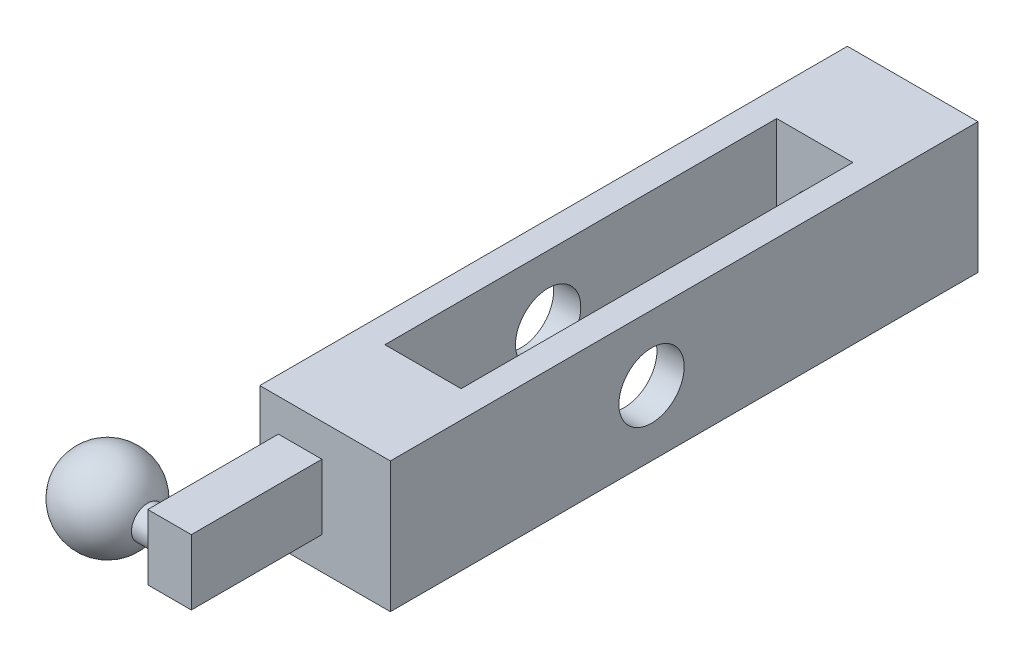
SolidWorks part; units mm, degrees
ref_plane "前视基准面" through (0, 0, 0) normal (0, 0, 1) x (1, 0, 0)
ref_plane "上视基准面" through (0, 0, 0) normal (0, 1, 0) x (1, 0, 0)
ref_plane "右视基准面" through (0, 0, 0) normal (1, 0, 0) x (0, 0, -1)
other "Configuration Table"
sketch "草图1" plane through (0, 0, 0) normal (0, 0, 1) x (1, 0, 0)
  line L1 (3, -3) -> (-3, -3)
  line L2 (3, -3) -> (3, 3)
  line L3 (3, 3) -> (-3, 3)
  line L4 (-3, -3) -> (-3, 3)
  line L5 (3, -3) -> (-3, 3) construction
  line L6 (3, 3) -> (-3, -3) construction
  point P0 (0, 0)
  dimension "D1" = 6
  dimension "D2" = 6
extrude "凸台-拉伸1" add sketch "草图1" along normal blind 27
sketch "草图2" plane through (0, 0, 27) normal (0, 0, 1) x (1, 0, 0)
  line L1 (-2.1448, 1.4955) -> (-0.1448, 1.4955)
  line L2 (-2.1448, 1.4955) -> (-2.1448, -1.5045)
  line L3 (-2.1448, -1.5045) -> (-0.1448, -1.5045)
  line L4 (-0.1448, 1.4955) -> (-0.1448, -1.5045)
  line L5 (-2.1448, 1.4955) -> (-0.1448, -1.5045) construction
  line L6 (-2.1448, -1.5045) -> (-0.1448, 1.4955) construction
  point P0 (-1.1448, -0.0045)
  dimension "D1" = 2
  dimension "D2" = 3
extrude "凸台-拉伸2" add sketch "草图2" along normal blind 6
sketch "草图3" plane through (-2.1448, 0, 0) normal (-1, 0, 0) x (0, 0, 1)
  circle A0 centre (32, 0) radius 0.75
  dimension "D1" = 1.5
  dimension "D2" = 32
extrude "凸台-拉伸3" add sketch "草图3" along normal blind 1
sketch "草图4" plane through (0, 0, 0) normal (0, 1, 0) x (1, 0, 0)
  line L0 (-3.1448, -32) -> (-6.9988, -32)
  line L1 (-3.1448, -31.25) -> (-3.1448, -32.75) construction
  line L2 (-3.1448, -32) -> (-3.1448, -31.25)
  arc A0 (-3.1448, -31.25) -> (-6.9988, -32) centre (-4.9988, -32) ccw
  dimension "D1" = 4
revolve "旋转1" add sketch "草图4" angle 360 about L0
sketch "草图5" plane through (0.5, 3, 0) normal (0, -1, 0) x (0, 0, 1)
  line L0 (27, 3.5) -> (0, 3.5) construction
  line L1 (4.5, 2.25) -> (22.5, 2.25)
  line L2 (4.5, 2.25) -> (4.5, -1.25)
  line L3 (4.5, -1.25) -> (22.5, -1.25)
  line L4 (22.5, 2.25) -> (22.5, -1.25)
  point P4 (4.5, 0.5)
  point P8 (13.5, 3.5)
  point P9 (13.5, 2.25)
  dimension "D1" = 18
  dimension "D2" = 3.5
extrude "切除-拉伸1" cut sketch "草图5" along normal blind 8
sketch "草图6" plane through (-3, 0, 0) normal (-1, 0, 0) x (0, 0, 1)
  line L0 (0, 3) -> (0, -3) construction
  circle A0 centre (15, 0) radius 1.5
  dimension "D1" = 3
  dimension "D2" = 15
extrude "切除-拉伸2" cut sketch "草图6" against normal blind 8
sketch "草图7" plane through (0, 0, 0) normal (0, 0, -1) x (-1, 0, 0)
  circle A0 centre (0, 0) radius 0.9
  dimension "D1" = 1.8
extrude "切除-拉伸3" cut sketch "草图7" against normal blind 8
